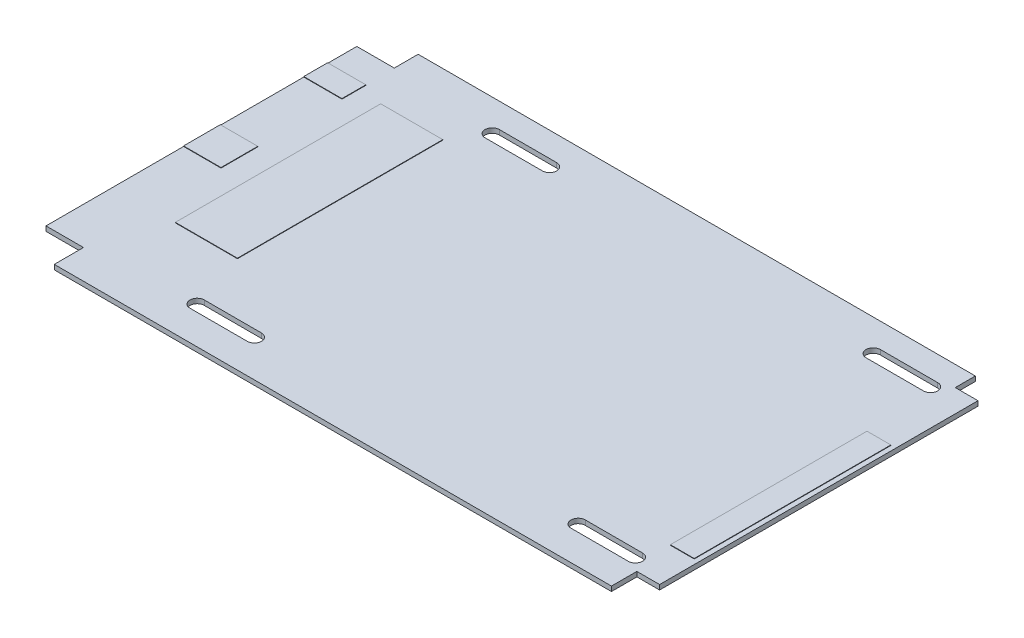
SolidWorks part; units mm, degrees
ref_plane "Alzado" through (0, 0, 0) normal (0, 0, 1) x (1, 0, 0)
ref_plane "Planta" through (0, 0, 0) normal (0, 1, 0) x (1, 0, 0)
ref_plane "Vista lateral" through (0, 0, 0) normal (1, 0, 0) x (0, 0, -1)
sketch "Croquis1" plane through (0, 0, 0) normal (0, 1, 0) x (1, 0, 0)
  line L0 (7.8422, -38.6563) -> (7.8423, -32.5437)
  line L2 (7.8423, -32.5437) -> (0, -32.5437)
  line L3 (0, -32.5437) -> (0, 32.5437)
  line L4 (0, 32.5437) -> (7.8422, 32.5437)
  line L5 (7.8422, 32.5437) -> (7.8422, 37.5437)
  line L6 (7.8422, 37.5437) -> (124.5235, 37.5437)
  line L7 (124.5235, 37.5437) -> (124.5235, 33.3375)
  line L8 (124.5235, 33.3375) -> (129.286, 33.3375)
  line L9 (129.286, 33.3375) -> (129.286, -33.3375)
  line L10 (129.286, -33.3375) -> (124.5235, -33.3375)
  line L11 (124.5235, -33.3375) -> (124.5235, -38.6562)
  line L12 (124.5235, -38.6562) -> (7.8422, -38.6563)
  point P3 (0, 0)
  point P4 (129.286, 0)
  dimension "D1" = 116.6813
  dimension "D3" = 65.0875
  dimension "D4" = 76.2
  dimension "D5" = 5
  dimension "D6" = 66.675
  dimension "D7" = 4.7625
  dimension "D8" = 129.286
extrude "Extruir1" add sketch "Croquis1" along normal mid plane 1
sketch "Croquis2" plane through (0, 0.5, 0) normal (0, 1, 0) x (1, 0, 0)
  line L0 (30, 30.9) -> (42, 30.9) construction
  line L1 (30, 32.4) -> (42, 32.4)
  line L2 (30, 29.4) -> (42, 29.4)
  line L4 (129.286, 0) -> (-18.9305, 0) construction
  line L5 (0, 32.5437) -> (0, -32.5437) construction
  line L6 (109.786, 30.9) -> (121.786, 30.9) construction
  line L7 (109.786, 32.4) -> (121.786, 32.4)
  line L8 (109.786, 29.4) -> (121.786, 29.4)
  line L9 (129.286, -33.3375) -> (129.286, 33.3375) construction
  arc A0 (30, 32.4) -> (30, 29.4) centre (30, 30.9) ccw
  arc A1 (42, 29.4) -> (42, 32.4) centre (42, 30.9) ccw
  arc A2 (109.786, 32.4) -> (109.786, 29.4) centre (109.786, 30.9) ccw
  arc A3 (121.786, 29.4) -> (121.786, 32.4) centre (121.786, 30.9) ccw
  point P2 (36, 30.9)
  point P13 (115.786, 30.9)
  dimension "D2" = 15
  dimension "D4" = 30
  dimension "D1" = 3
  dimension "D3" = 30.9
  dimension "D5" = 3
  dimension "D6" = 15
  dimension "D8" = 7.5
extrude "Extruir2" cut sketch "Croquis2" against normal through all
mirror "Simetría1" about plane through (0, 0, 0) normal (0, 0, 1) of "Extruir2"
sketch "Croquis3" plane through (0, 0.5, 0) normal (0, 1, 0) x (1, 0, 0)
  line L0 (0, 32.5437) -> (0, -32.5437) construction
  line L1 (0, 3.9624) -> (7.8422, 3.9624)
  line L2 (0, 3.9624) -> (0, -3.7376)
  line L3 (0, -3.7376) -> (7.8422, -3.7376)
  line L4 (7.8422, 3.9624) -> (7.8422, -3.7376)
  line L6 (7.8422, 37.5437) -> (7.8422, 32.5437) construction
  line L7 (124.5235, 37.5437) -> (7.8422, 37.5437) construction
  line L8 (13, 24.5437) -> (26, 24.5437)
  line L9 (13, 24.5437) -> (13, -18.4562)
  line L10 (13, -18.4562) -> (26, -18.4562)
  line L11 (26, 24.5437) -> (26, -18.4562)
  line L13 (0, 26.4312) -> (8, 26.4312)
  line L14 (0, 26.4312) -> (0, 21.4312)
  line L15 (0, 21.4312) -> (8, 21.4312)
  line L16 (8, 26.4312) -> (8, 21.4312)
  line L17 (124.5235, -33.3375) -> (129.286, -33.3375) construction
  line L18 (123.286, 16.0875) -> (128.286, 16.0875)
  line L19 (123.286, 16.0875) -> (123.286, -25.0875)
  line L20 (123.286, -25.0875) -> (128.286, -25.0875)
  line L21 (128.286, 16.0875) -> (128.286, -25.0875)
  line L22 (129.286, -33.3375) -> (129.286, 33.3375) construction
  dimension "D2" = 7.7
  dimension "D3" = 13
  dimension "D4" = 43
  dimension "D5" = 13
  dimension "D6" = 13
  dimension "D7" = 11.1125
  dimension "D8" = 5
  dimension "D9" = 8
  dimension "D10" = 8.25
  dimension "D11" = 1
  dimension "D12" = 41.175
  dimension "D13" = 5
  dimension "D18" = 17.4688
extrude "Extruir3" add sketch "Croquis3" along normal blind 0.1
